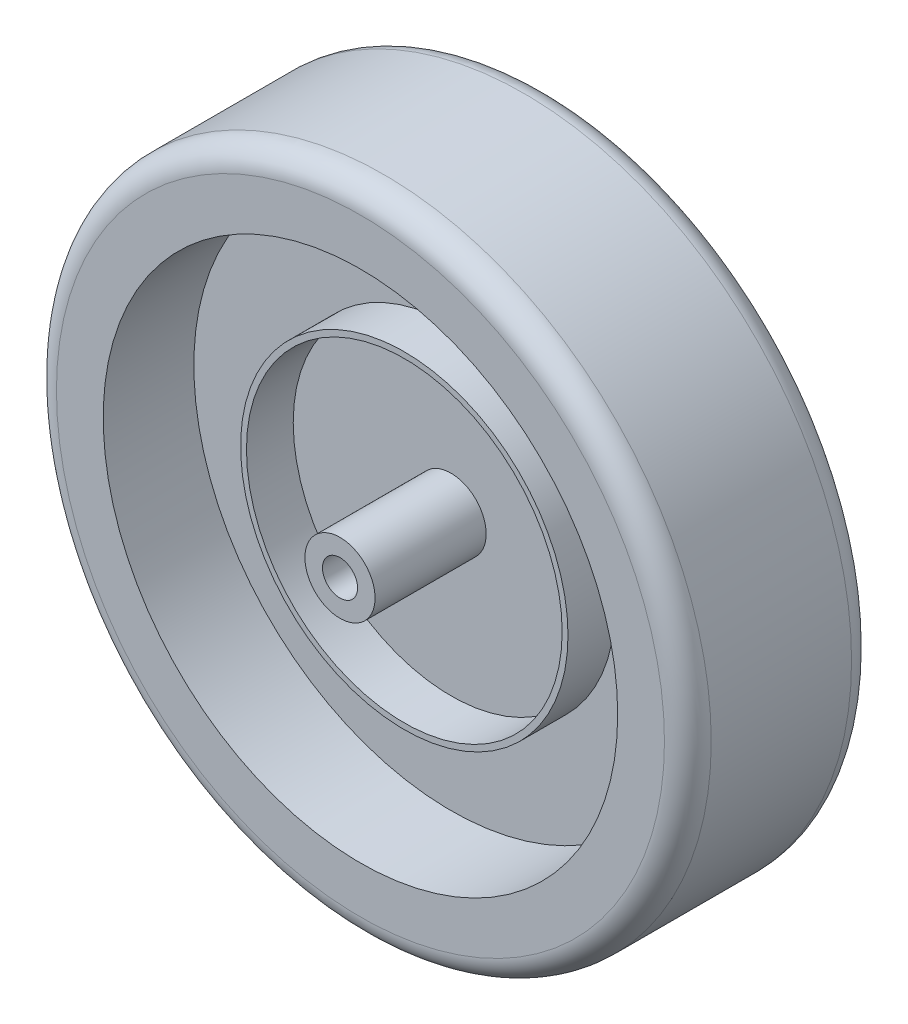
SolidWorks part; units mm, degrees
ref_plane "Front" through (0, 0, 0) normal (0, 0, 1) x (1, 0, 0)
ref_plane "Top" through (0, 0, 0) normal (0, 1, 0) x (1, 0, 0)
ref_plane "Right" through (0, 0, 0) normal (1, 0, 0) x (0, 0, -1)
sketch "Sketch1" plane through (0, 0, 0) normal (0, 0, 1) x (1, 0, 0)
  circle A0 centre (0, 0) radius 88.9
  circle A1 centre (0, 0) radius 69.85
  dimension "D1" = 177.8
  dimension "D2" = 19.05
extrude "Extrude1" add sketch "Sketch1" along normal mid plane 50.8
fillet "Fillet1" radius 6.35 2 edges at (88.9, 0, -25.4) (88.9, 0, 25.4)
sketch "Sketch2" plane through (0, 0, 0) normal (0, 0, 1) x (1, 0, 0)
  circle A0 centre (0, 0) radius 9.525
  circle A1 centre (0, 0) radius 69.85
  circle A2 centre (0, 0) radius 69.85 construction
  dimension "D1" = 19.05
extrude "Extrude2" add sketch "Sketch2" along normal mid plane 1.5875
sketch "Sketch3" plane through (0, 0, 0.7937) normal (0, 0, 1) x (1, 0, 0)
  circle A0 centre (0, 0) radius 9.525 construction
  circle A1 centre (0, 0) radius 9.525
  circle A2 centre (0, 0) radius 4.7625
  dimension "D1" = 9.525
extrude "Extrude3" add sketch "Sketch3" along normal mid plane 60.325
sketch "Sketch4" plane through (0, 0, 0.7937) normal (0, 0, 1) x (1, 0, 0)
  circle A0 centre (0, 0) radius 44.45
  circle A1 centre (0, 0) radius 42.8625
  dimension "D1" = 1.5875
  dimension "D2" = 88.9
extrude "Extrude4" add sketch "Sketch4" along normal mid plane 25.4
sketch3d "3DSketch1"
  line L0 (0, 0, 30.9562) -> (0, 0, -29.3687) construction
  line L1 (0, 0, -0.7938) -> (0, 0, -29.3687) construction
  point P0 (0, 0, 30.9562)
  point P1 (0, 0, -29.3687)
